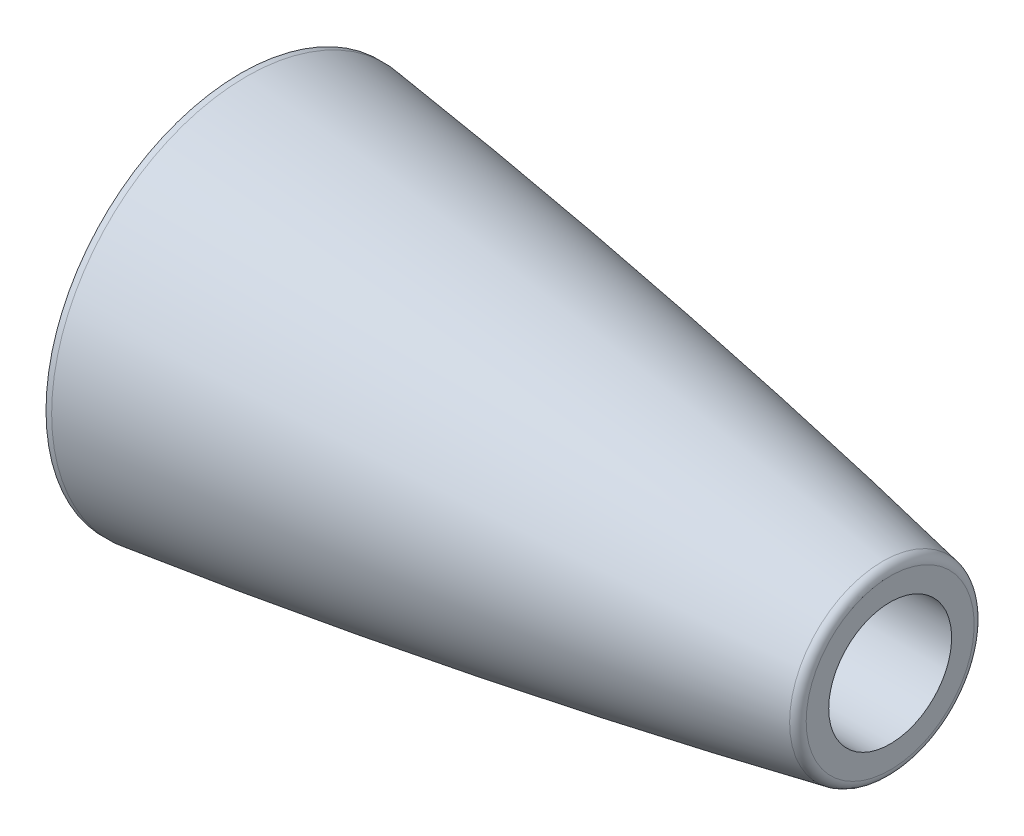
SolidWorks part; units mm, degrees
ref_plane "Plano frontal" through (0, 0, 0) normal (0, 0, 1) x (1, 0, 0)
ref_plane "Plano superior" through (0, 0, 0) normal (0, 1, 0) x (1, 0, 0)
ref_plane "Plano direito" through (0, 0, 0) normal (1, 0, 0) x (0, 0, -1)
sketch "Esboço1" plane through (0, 0, 0) normal (0, 0, 1) x (1, 0, 0)
  line L0 (10.25, 1.665) -> (10.25, 1.325)
  line L1 (14, 1.8108) -> (14, 1.325)
  line L2 (0, 0) -> (12.557, 0) construction
  line L3 (10.25, 1.325) -> (14, 1.325)
  line L5 (0, 3.2074) -> (0, 4.2)
  line L6 (0.1215, 4.2) -> (0, 4.2)
  line L7 (0, 3.2074) -> (3.7671, 3.002)
  line L9 (3.7671, 3.002) -> (10.25, 1.665)
  arc A0 (0.1215, 4.2) -> (13.8388, 2.007) centre (-22.8767, -183.648) cw
  arc A4 (13.8388, 2.007) -> (14, 1.8108) centre (13.8, 1.8108) cw
  point P1 (14, 1.975)
  point P3 (14, 0)
  point P8 (-22.8767, -183.648)
  point P10 (13, 1.1523)
  dimension "D7" = 0.2
  dimension "D2" = 189.2506
  dimension "D8" = 3.121
  dimension "D1" = 8.4
  dimension "D4" = 14
  dimension "D5" = 2.65
  dimension "D6" = 10.25
  dimension "D9" = 1.665
  dimension "D3" = 3.002
  dimension "D10" = 11.653
revolve "Revolução1" add sketch "Esboço1" angle 360 about L2
